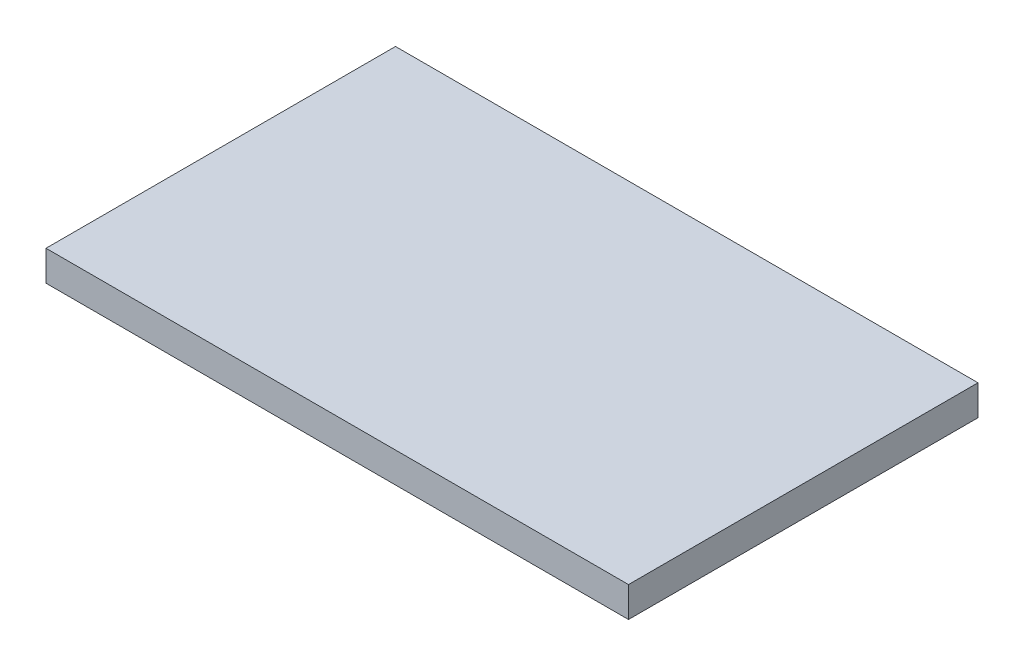
SolidWorks part; units mm, degrees
ref_plane "Front Plane" through (0, 0, 0) normal (0, 0, 1) x (1, 0, 0)
ref_plane "Top Plane" through (0, 0, 0) normal (0, 1, 0) x (1, 0, 0)
ref_plane "Right Plane" through (0, 0, 0) normal (1, 0, 0) x (0, 0, -1)
sketch "Sketch1" plane through (0, 0, 0) normal (0, 1, 0) x (1, 0, 0)
  line L1 (-12.5, 7.5) -> (12.5, 7.5)
  line L2 (-12.5, 7.5) -> (-12.5, -7.5)
  line L3 (-12.5, -7.5) -> (12.5, -7.5)
  line L4 (12.5, 7.5) -> (12.5, -7.5)
  line L5 (-12.5, 7.5) -> (12.5, -7.5) construction
  line L6 (-12.5, -7.5) -> (12.5, 7.5) construction
  point P0 (0, 0)
  dimension "D1" = 15
  dimension "D2" = 25
extrude "Boss-Extrude1" add sketch "Sketch1" along normal blind 1.3
sketch "Sketch2" plane through (0, 1.3, 0) normal (0, 1, 0) x (1, 0, 0)
  line L0 (-3.6547, -5.4893) -> (-12.0308, -5.4893)
  line L1 (-3.6547, -5.4893) -> (-3.6547, 2.4262)
  line L2 (-3.6547, 2.4262) -> (-4.3547, 2.4262)
  line L3 (-4.3547, 2.4262) -> (-4.3547, -4.7893)
  line L4 (-4.3547, -4.7893) -> (-11.3308, -4.7893)
  line L5 (-11.3308, -4.7893) -> (-11.3308, -4.0893)
  line L6 (-11.3308, -4.0893) -> (-6.5579, -4.0893)
  line L7 (-6.5579, -4.0893) -> (-6.5579, -2.7854)
  line L8 (-6.5579, -2.7854) -> (-11.3605, -2.7854)
  line L9 (-11.3605, -2.7854) -> (-11.3605, -2)
  line L10 (-11.3605, -2) -> (-6.7412, -2)
  line L11 (-6.7412, -2) -> (-6.7412, 0)
  line L12 (-6.7412, 0) -> (-11.3308, 0)
  line L13 (-11.3308, 0) -> (-11.3308, 1.9952)
  line L15 (-12.0308, -5.4893) -> (-12.0308, -3.3893)
  line L16 (-12.0308, -3.3893) -> (-7.2579, -3.3893)
  line L17 (-7.2579, -3.3893) -> (-7.2579, -3.2778)
  line L18 (-7.2579, -3.2778) -> (-12.0717, -3.2778)
  line L19 (-12.0717, -3.2778) -> (-12.0717, -1.3)
  line L20 (-12.0717, -1.3) -> (-7.3317, -1.3)
  line L21 (-7.3317, -1.3) -> (-7.3317, -0.7)
  line L22 (-7.3317, -0.7) -> (-12.0308, -0.7)
  line L23 (-12.0308, -0.7) -> (-12.0308, 2.6952)
  line L24 (-12.0308, 2.6952) -> (-6.7412, 2.6952)
  line L25 (-6.7412, 2.6952) -> (-6.7412, 3.2952)
  line L26 (-6.7412, 3.2952) -> (-12.0308, 3.2952)
  line L27 (-12.0308, 3.2952) -> (-12.0308, 6.9749)
  line L28 (-12.0308, 6.9749) -> (-11.3308, 6.9749)
  line L29 (-11.3308, 6.9749) -> (-11.3308, 3.9952)
  line L30 (-11.3308, 3.9952) -> (-6.0904, 3.9952)
  line L31 (-6.0904, 3.9952) -> (-6.0904, 1.9952)
  line L32 (-6.0904, 1.9952) -> (-11.3308, 1.9952)
  dimension "D1" = 0.7
  dimension "D2" = 2
  dimension "D3" = 2
  dimension "D4" = 1.304
  dimension "D5" = 0.7
  dimension "D6" = 0.1115
  dimension "D7" = 1.9952
  dimension "D8" = 0.7
  dimension "D11" = 0.7
  dimension "D12" = 0.7
  dimension "D13" = 0.7
  dimension "D14" = 0.7
  dimension "D15" = 0.7
  dimension "D17" = 0.7
